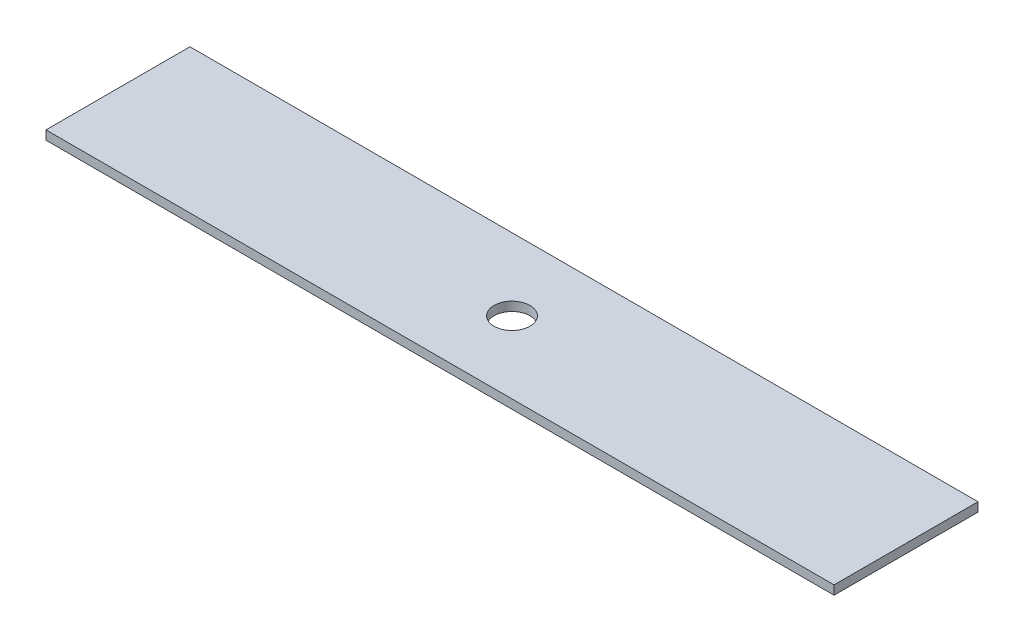
SolidWorks part; units mm, degrees
ref_plane "Front Plane" through (0, 0, 0) normal (0, 0, 1) x (1, 0, 0)
ref_plane "Top Plane" through (0, 0, 0) normal (0, 1, 0) x (1, 0, 0)
ref_plane "Right Plane" through (0, 0, 0) normal (1, 0, 0) x (0, 0, -1)
sketch "Sketch1" plane through (0, 0, 0) normal (0, 1, 0) x (1, 0, 0)
  line L1 (-139.065, 25.4) -> (139.065, 25.4)
  line L2 (-139.065, 25.4) -> (-139.065, -25.4)
  line L3 (-139.065, -25.4) -> (139.065, -25.4)
  line L4 (139.065, 25.4) -> (139.065, -25.4)
  line L5 (-139.065, 25.4) -> (139.065, -25.4) construction
  line L6 (-139.065, -25.4) -> (139.065, 25.4) construction
  point P0 (0, 0)
  dimension "D1" = 278.13
extrude "Boss-Extrude1" add sketch "Sketch1" along normal blind 3.175
sketch "Sketch2" plane through (0, 3.175, 0) normal (0, 1, 0) x (1, 0, 0)
  circle A0 centre (0, 0) radius 6.35
extrude "Cut-Extrude1" cut sketch "Sketch2" against normal through all
